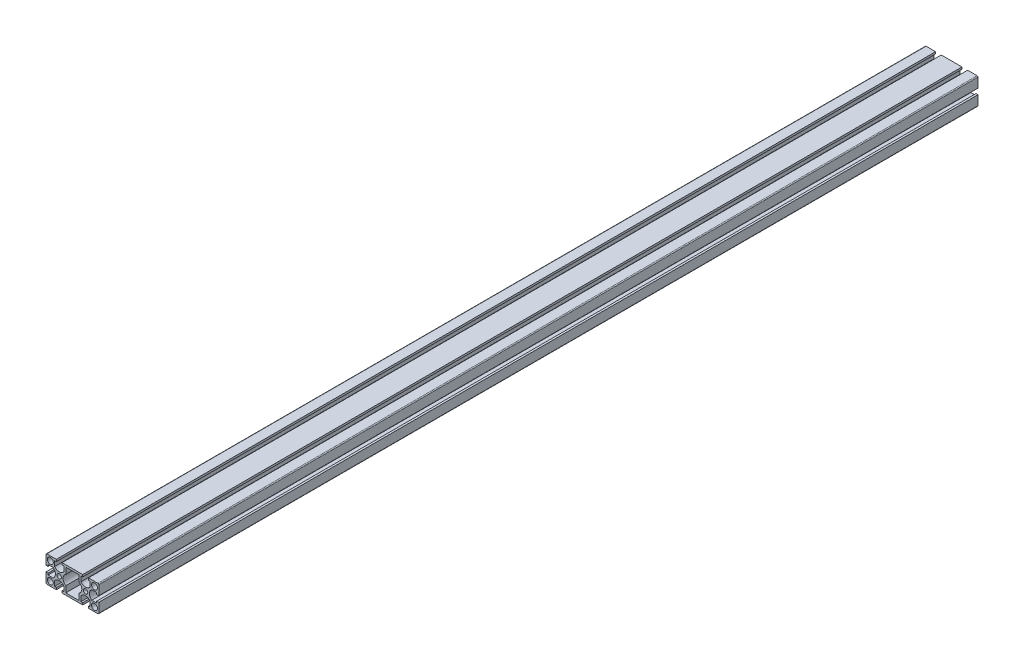
SolidWorks part; units mm, degrees
ref_plane "前视基准面" through (0, 0, 0) normal (0, 0, 1) x (1, 0, 0)
ref_plane "上视基准面" through (0, 0, 0) normal (0, 1, 0) x (1, 0, 0)
ref_plane "右视基准面" through (0, 0, 0) normal (1, 0, 0) x (0, 0, -1)
sketch "草图1" plane through (0, 0, 0) normal (0, 0, 1) x (1, 0, 0)
  line L0 (-17.2043, -18.1182) -> (6.2957, -18.1182)
  line L1 (-25.6543, -15.8182) -> (-23.7043, -15.8182)
  line L2 (-17.2043, -15.8182) -> (-15.2543, -15.8182)
  line L3 (-17.2043, -15.8182) -> (-17.2043, -18.1182)
  line L4 (-23.7043, -15.8182) -> (-23.7043, -18.1182)
  line L5 (-15.2543, -15.8182) -> (-15.2543, -10.0182)
  line L6 (-25.6543, -15.8182) -> (-25.6543, -10.0182)
  line L7 (-23.7043, -18.1182) -> (-34.4543, -18.1182)
  line L8 (-35.4543, -17.1182) -> (-35.4543, -6.3682)
  line L9 (-33.1543, -8.3182) -> (-33.1543, -6.3682)
  line L10 (-33.1543, -6.3682) -> (-35.4543, -6.3682)
  line L11 (-33.1543, -8.3182) -> (-27.3543, -8.3182)
  line L12 (-17.2043, 11.8818) -> (6.2957, 11.8818)
  line L13 (-25.6543, 9.5818) -> (-23.7043, 9.5818)
  line L14 (-17.2043, 9.5818) -> (-15.2543, 9.5818)
  line L15 (-17.2043, 9.5818) -> (-17.2043, 11.8818)
  line L16 (-23.7043, 9.5818) -> (-23.7043, 11.8818)
  line L17 (-15.2543, 9.5818) -> (-15.2543, 3.7818)
  line L18 (-25.6543, 9.5818) -> (-25.6543, 3.7818)
  line L19 (-23.7043, 11.8818) -> (-34.4543, 11.8818)
  line L20 (-35.4543, 10.8818) -> (-35.4543, 0.1318)
  line L21 (-33.1543, 2.0818) -> (-33.1543, 0.1318)
  line L22 (-33.1543, 0.1318) -> (-35.4543, 0.1318)
  line L23 (-33.1543, 2.0818) -> (-27.3543, 2.0818)
  line L25 (6.2957, -18.1182) -> (6.2957, -15.8182)
  line L26 (6.2957, -15.8182) -> (4.3457, -15.8182)
  line L27 (4.3457, -15.8182) -> (4.3457, -10.0182)
  line L28 (14.7457, -10.0182) -> (14.7457, -15.8182)
  line L29 (14.7457, -15.8182) -> (12.7957, -15.8182)
  line L30 (12.7957, -15.8182) -> (12.7957, -18.1182)
  line L31 (12.7957, -18.1182) -> (23.5457, -18.1182)
  line L32 (24.5457, -17.1182) -> (24.5457, -6.3682)
  line L33 (24.5457, -6.3682) -> (22.2457, -6.3682)
  line L34 (22.2457, -6.3682) -> (22.2457, -8.3182)
  line L35 (22.2457, -8.3182) -> (16.4457, -8.3182)
  line L36 (16.4457, 2.0818) -> (22.2457, 2.0818)
  line L37 (22.2457, 2.0818) -> (22.2457, 0.1318)
  line L38 (22.2457, 0.1318) -> (24.5457, 0.1318)
  line L39 (24.5457, 0.1318) -> (24.5457, 10.8818)
  line L40 (23.5457, 11.8818) -> (12.7957, 11.8818)
  line L41 (12.7957, 11.8818) -> (12.7957, 9.5818)
  line L42 (12.7957, 9.5818) -> (14.7457, 9.5818)
  line L43 (14.7457, 9.5818) -> (14.7457, 3.7818)
  line L44 (4.3457, 3.7818) -> (4.3457, 9.5818)
  line L45 (4.3457, 9.5818) -> (6.2957, 9.5818)
  line L46 (6.2957, 9.5818) -> (6.2957, 11.8818)
  line L48 (2.0457, -15.8182) -> (2.0457, -8.7182)
  line L49 (2.0457, 2.4818) -> (2.0457, 9.5818)
  line L50 (-12.9543, -15.8182) -> (-12.9543, -8.7182)
  line L51 (-12.9543, 2.4818) -> (-12.9543, 9.5818)
  line L52 (-12.9543, 9.5818) -> (2.0457, 9.5818)
  line L53 (-12.9543, -15.8182) -> (2.0457, -15.8182)
  circle A0 centre (-20.4543, -3.1182) radius 2.5
  circle A1 centre (-30.5543, -13.2182) radius 3.4
  circle A2 centre (-30.5543, 6.9818) radius 3.4
  arc A3 (-15.2543, -10.0182) -> (-25.6543, -10.0182) centre (-20.4543, -13.9182) ccw
  arc A4 (-35.4543, -17.1182) -> (-34.4543, -18.1182) centre (-34.4543, -17.1182) ccw
  arc A5 (-27.3543, -8.3182) -> (-27.3543, 2.0818) centre (-31.2543, -3.1182) ccw
  arc A6 (-25.6543, 3.7818) -> (-15.2543, 3.7818) centre (-20.4543, 7.6818) ccw
  arc A7 (-34.4543, 11.8818) -> (-35.4543, 10.8818) centre (-34.4543, 10.8818) ccw
  arc A8 (-12.9543, 2.4818) -> (-12.9543, -8.7182) centre (-9.6543, -3.1182) ccw
  circle A9 centre (19.6457, -13.2182) radius 3.4
  circle A10 centre (19.6457, 6.9818) radius 3.4
  arc A11 (2.0457, -8.7182) -> (2.0457, 2.4818) centre (-1.2543, -3.1182) ccw
  arc A12 (14.7457, -10.0182) -> (4.3457, -10.0182) centre (9.5457, -13.9182) ccw
  arc A13 (23.5457, -18.1182) -> (24.5457, -17.1182) centre (23.5457, -17.1182) ccw
  arc A14 (16.4457, 2.0818) -> (16.4457, -8.3182) centre (20.3457, -3.1182) ccw
  arc A15 (24.5457, 10.8818) -> (23.5457, 11.8818) centre (23.5457, 10.8818) ccw
  arc A16 (4.3457, 3.7818) -> (14.7457, 3.7818) centre (9.5457, 7.6818) ccw
  circle A17 centre (9.5457, -3.1182) radius 2.5
extrude "凸台-拉伸1" add sketch "草图1" along normal blind 1000
